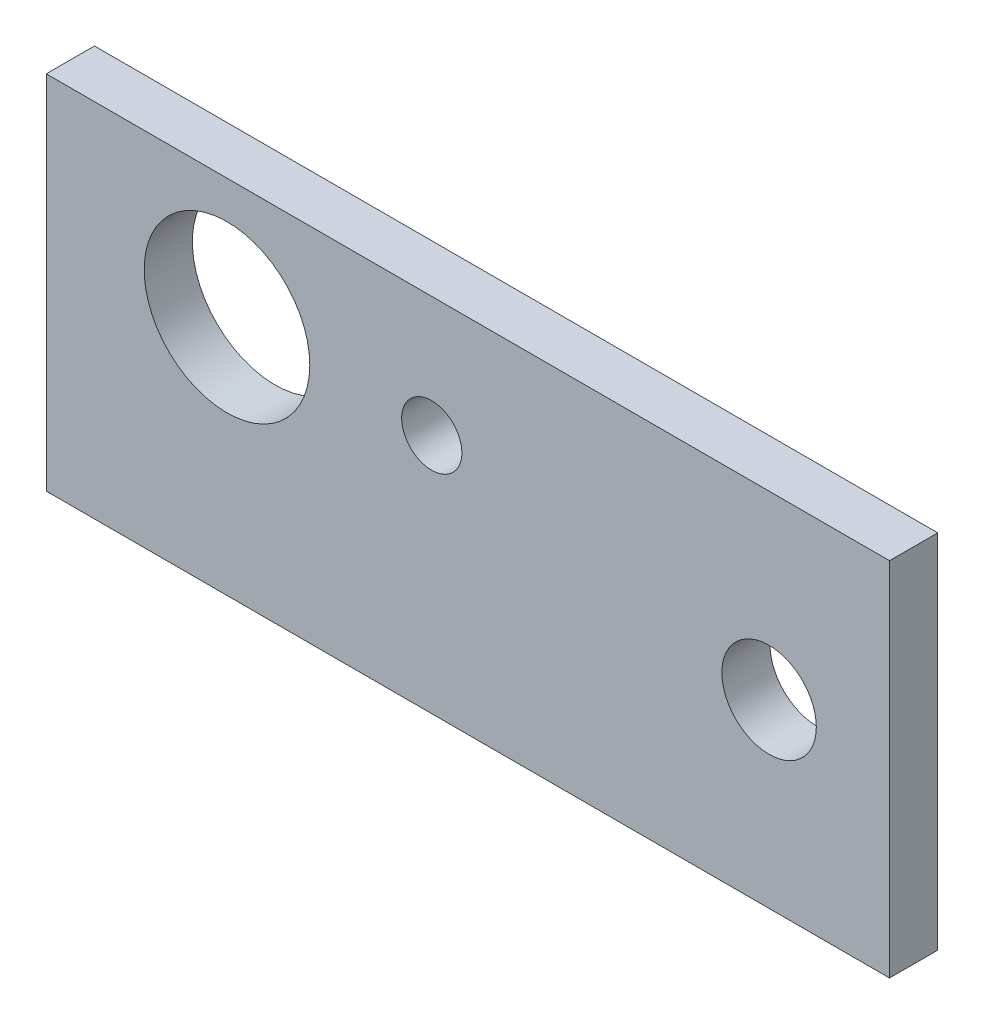
SolidWorks part; units mm, degrees
material "Plain Carbon Steel"
ref_plane "Front Plane" through (0, 0, 0) normal (0, 0, 1) x (1, 0, 0)
ref_plane "Top Plane" through (0, 0, 0) normal (0, 1, 0) x (1, 0, 0)
ref_plane "Right Plane" through (0, 0, 0) normal (1, 0, 0) x (0, 0, -1)
sketch "Sketch1" plane through (0, 0, 0) normal (0, 0, 1) x (1, 0, 0)
  line L1 (-22.225, 9.525) -> (22.225, 9.525)
  line L2 (-22.225, 9.525) -> (-22.225, -9.525)
  line L3 (-22.225, -9.525) -> (22.225, -9.525)
  line L4 (22.225, 9.525) -> (22.225, -9.525)
  line L5 (-22.225, 9.525) -> (22.225, -9.525) construction
  line L6 (-22.225, -9.525) -> (22.225, 9.525) construction
  point P0 (0, 0)
  dimension "D1" = 44.45
  dimension "D2" = 19.05
extrude "Boss-Extrude1" add sketch "Sketch1" along normal blind 2.54
sketch "Sketch2" plane through (0, 0, 2.54) normal (0, 0, 1) x (1, 0, 0)
  line L0 (22.225, 9.525) -> (-22.225, 9.525) construction
  line L1 (-22.225, 9.525) -> (-22.225, -9.525) construction
  line L2 (22.225, -9.525) -> (22.225, 9.525) construction
  line L6 (-22.225, -9.525) -> (22.225, -9.525) construction
  circle A0 centre (-12.7, 3.175) radius 4.3656
  circle A1 centre (-1.905, 3.175) radius 1.5875
  circle A2 centre (15.875, 0) radius 2.4892
  dimension "D1" = 8.7312
  dimension "D4" = 4.9784
  dimension "D5" = 6.35
  dimension "D6" = 9.525
  dimension "D7" = 10.795
  dimension "D9" = 3.175
  dimension "D8" = 6.35
  dimension "D2" = 6.35
  dimension "D3" = 9.525
extrude "Cut-Extrude1" cut sketch "Sketch2" against normal up to next
